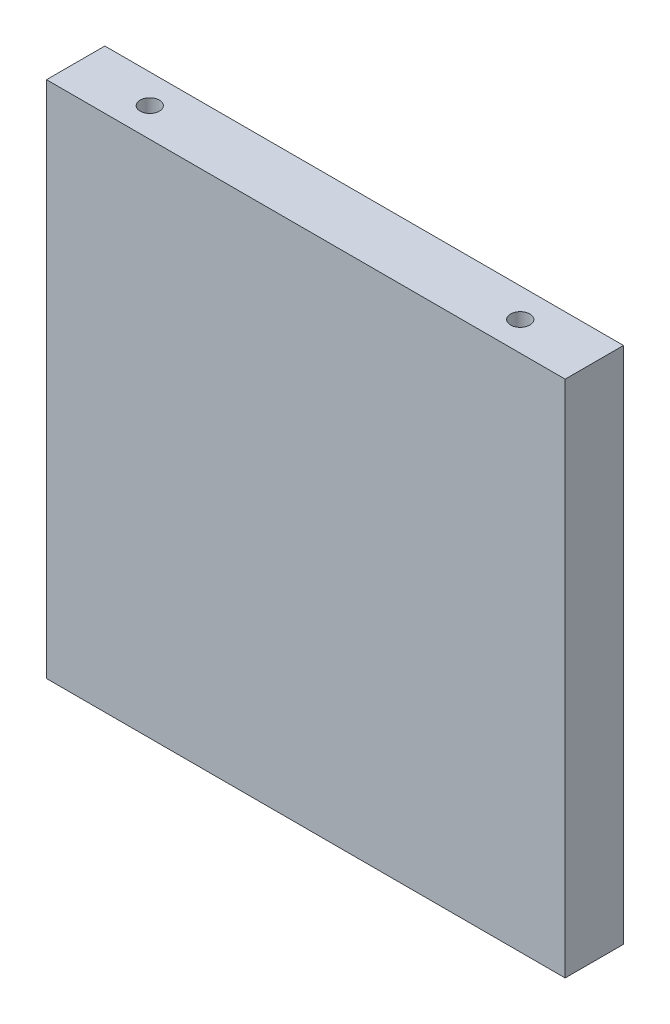
SolidWorks part; units mm, degrees
ref_plane "Front" through (0, 0, 0) normal (0, 0, 1) x (1, 0, 0)
ref_plane "Top" through (0, 0, 0) normal (0, 1, 0) x (1, 0, 0)
ref_plane "Right" through (0, 0, 0) normal (1, 0, 0) x (0, 0, -1)
sketch "Sketch1" plane through (0, 0, 0) normal (0, 1, 0) x (1, 0, 0)
  line L0 (44.45, 10) -> (44.45, 0)
  line L1 (0, 0) -> (88.9, 0)
  line L2 (0, 0) -> (0, 10)
  line L3 (0, 10) -> (88.9, 10)
  line L4 (88.9, 0) -> (88.9, 10)
  line L5 (12.7, 5) -> (76.2, 5)
  circle A0 centre (12.7, 5) radius 1.65
  circle A1 centre (76.2, 5) radius 1.65
  point P10 (44.45, 5)
  dimension "D1" = 88.9
  dimension "D2" = 10
  dimension "D3" = 63.5
extrude "Boss-Extrude1" add sketch "Sketch1" along normal blind 88.9
